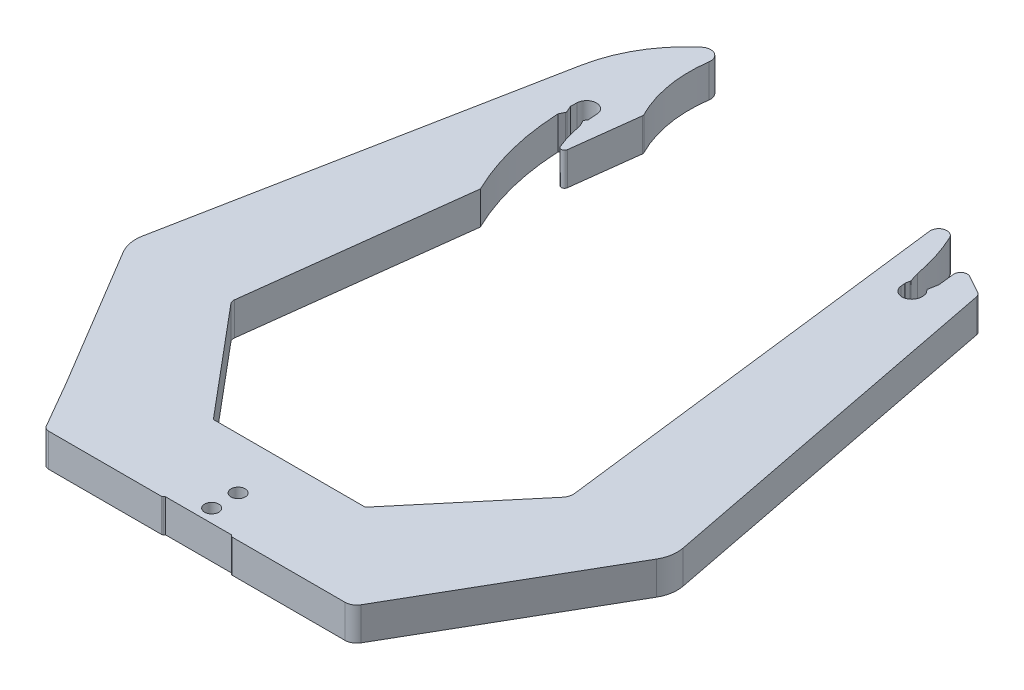
SolidWorks part; units mm, degrees
ref_plane "前视基准面" through (0, 0, 0) normal (0, 0, 1) x (1, 0, 0)
ref_plane "上视基准面" through (0, 0, 0) normal (0, 1, 0) x (1, 0, 0)
ref_plane "右视基准面" through (0, 0, 0) normal (1, 0, 0) x (0, 0, -1)
sketch "草图1" plane through (0, 0, 0) normal (0, 1, 0) x (1, 0, 0)
  line L0 (0, 0) -> (0, -28) construction
  line L1 (-23, 0) -> (23, 0)
  line L2 (-46.9156, -28) -> (46.9156, -28) construction
  line L3 (23, 0) -> (50.2804, 32.5116)
  line L4 (51.0926, 35.2535) -> (36.049, 157.7742)
  line L5 (47.9507, -26.2071) -> (80.6721, 30.468)
  line L6 (81.8281, 37.3761) -> (60.3948, 147.6409)
  line L7 (-10, -27.5) -> (10, -27.5)
  line L8 (10, -27.5) -> (10.3536, -27.8536)
  line L9 (10.7071, -28) -> (44.8453, -28)
  line L10 (-10, -27.5) -> (-10.3536, -27.8536)
  line L11 (-10.7071, -28) -> (-44.8453, -28)
  line L12 (-46.9156, -28) -> (-80.6721, 30.468) construction
  line L13 (-23, 0) -> (-50.7237, 33.0398)
  line L14 (-51.2827, 33.706) -> (-36.049, 157.7742) construction
  line L15 (-81.8281, 37.3761) -> (-60.2169, 148.5563)
  line L16 (52.0874, 139.7007) -> (51.9688, 140.8286)
  line L17 (53.9563, 152.0266) -> (59.4012, 149.0085)
  line L18 (-37.6333, 144.8711) -> (-51.1767, 34.5691)
  line L26 (-80.6721, 30.468) -> (-54.7279, -12.8828)
  line L27 (-54.7279, -12.8828) -> (-46.5774, -27)
  line L29 (51.518, 145.1181) -> (50.9977, 150.0683)
  line L38 (45.9622, 140.5216) -> (46.0104, 140.2189)
  line L40 (45.9622, 140.5216) -> (46.2393, 141.7564)
  line L41 (46.2287, 142.015) -> (45.3363, 144.8711)
  line L42 (51.518, 145.1181) -> (51.0019, 142.3738)
  line L43 (51.0952, 141.979) -> (51.9688, 140.8286)
  arc A0 (80.6721, 30.468) -> (81.8281, 37.3761) centre (72.0119, 35.468) ccw
  arc A1 (-80.6721, 30.468) -> (-81.8281, 37.3761) centre (-72.0119, 35.468) cw
  arc A2 (36.049, 157.7742) -> (40.7995, 159.1281) centre (38.5304, 158.0789) cw
  arc A3 (40.7995, 159.1281) -> (45.3363, 144.8711) centre (-13.661, 133.9476) cw
  arc A4 (46.115, 139.1281) -> (52.0874, 139.7007) centre (49.1038, 139.3871) ccw
  arc A5 (60.3948, 147.6409) -> (59.4012, 149.0085) centre (58.4316, 147.2592) ccw
  arc A6 (50.9977, 150.0683) -> (53.9563, 152.0266) centre (52.9867, 150.2774) cw
  arc A7 (-60.2169, 148.5563) -> (-46.6353, 171.5892) centre (-20.9518, 140.924) cw
  arc A8 (-46.6353, 171.5892) -> (-41.7383, 168.8711) centre (-44.709, 169.2893) cw
  arc A9 (-41.7383, 168.8711) -> (-37.6333, 144.8711) centre (-2.1289, 163.295) ccw
  arc A10 (-50.7237, 33.0398) -> (-51.1767, 34.5691) centre (-49.1916, 34.3254) cw
  arc A19 (47.9507, -26.2071) -> (44.8453, -28) centre (44.8453, -24.4141) cw
  arc A20 (50.2804, 32.5116) -> (51.0926, 35.2535) centre (47.5335, 34.8165) ccw
  arc A21 (10.3536, -27.8536) -> (10.7071, -28) centre (10.7071, -27.5) ccw
  arc A22 (-10.3536, -27.8536) -> (-10.7071, -28) centre (-10.7071, -27.5) cw
  arc A23 (-44.8453, -28) -> (-46.5774, -27) centre (-44.8453, -26) cw
  arc A29 (46.0104, 140.2189) -> (46.115, 139.1281) centre (-13.661, 133.9476) cw
  arc A32 (51.0019, 142.3738) -> (51.0952, 141.979) centre (51.4933, 142.2814) ccw
  arc A33 (46.2393, 141.7564) -> (46.2287, 142.015) centre (45.7514, 141.8658) ccw
  point P7 (0, 0)
  point P9 (0, -28)
  point P18 (82.5415, 33.706)
  point P24 (0, -27.5)
  point P50 (60.2169, 148.5563)
  point P53 (50.5961, 153.8892)
  point P56 (50.9609, 142.1557)
  point P65 (46.2686, 141.8871)
  point P76 (-54.6473, -14.6083)
  point P85 (51.2827, 33.706)
  point P88 (10.5, -28)
  point P91 (-10.5, -28)
  dimension "D14" = 10
  dimension "D17" = 2.5
  dimension "D18" = 3
  dimension "D20" = 60
  dimension "D22" = 2
  dimension "D23" = 40
  dimension "D24" = 3
  dimension "D26" = 40
  dimension "D30" = 2
  dimension "D39" = 0.5
  dimension "D28" = 2
  dimension "D33" = 150
  dimension "D34" = 4.7
  dimension "D35" = 0.5
  dimension "D1" = 28
  dimension "D2" = 46
  dimension "D4" = 130
  dimension "D5" = 44
  dimension "D6" = 133
  dimension "D7" = 125
  dimension "D8" = 120
  dimension "D9" = 139
  dimension "D10" = 117
  dimension "D11" = 10
  dimension "D12" = 1
  dimension "D13" = 135
  dimension "D15" = 130
  dimension "D16" = 55
  dimension "D19" = 20
  dimension "D21" = 11
  dimension "D25" = 13
  dimension "D27" = 24
  dimension "D29" = 34.1382
  dimension "D31" = 34.1382
extrude "凸台-拉伸1" add sketch "草图1" along normal blind 10
sketch "草图2" plane through (0, 10, 0) normal (0, 1, 0) x (1, 0, 0)
  line L0 (-51.1767, 34.5691) -> (-37.6333, 144.8711) construction
  line L1 (-44.9653, 137.163) -> (-44.8045, 135.3458)
  line L2 (-40.5801, 120.8711) -> (-43.0358, 100.8711)
  line L3 (-10, -27.5) -> (10, -27.5) construction
  line L4 (23, 0) -> (-23, 0) construction
  line L5 (-51.0321, 136.1605) -> (-50.2132, 134.2715)
  line L6 (-50.2197, 133.8595) -> (-50.959, 132.2906)
  line L7 (-44.8045, 135.3458) -> (-45.2779, 134.5968)
  line L8 (-45.298, 134.0972) -> (-44.4522, 132.4865)
  arc A0 (-43.0358, 100.8711) -> (-50.959, 132.2906) centre (28.9667, 135.7371) cw
  arc A1 (-50.9987, 138.0882) -> (-45.0011, 138.0823) centre (-48, 138) cw
  arc A2 (-45.0011, 138.0823) -> (-44.9653, 137.163) centre (-5.0162, 139.1798) ccw
  circle A3 centre (0, -23.5) radius 2.15
  circle A4 centre (0, -15.5) radius 2.15
  arc A7 (-44.4522, 132.4865) -> (-40.5801, 120.8711) centre (-5.0162, 139.1798) ccw
  arc A9 (-45.2779, 134.5968) -> (-45.298, 134.0972) centre (-44.8553, 134.3297) ccw
  arc A10 (-50.2132, 134.2715) -> (-50.2197, 133.8595) centre (-50.672, 134.0727) cw
  arc A11 (-51.0321, 136.1605) -> (-50.9987, 138.0882) centre (28.9667, 135.7371) cw
  point P28 (-45.4343, 134.3568)
  point P32 (-45.4322, 134.3528)
  point P35 (-50.1233, 134.0641)
  dimension "D5" = 3
  dimension "D6" = 138
  dimension "50" = 40
  dimension "D7" = 80
  dimension "D9" = 4.3
  dimension "D12" = 4.7
  dimension "D14" = 0.5
  dimension "D2" = 20
  dimension "D3" = 24
  dimension "D4" = 48
  dimension "D8" = 8
  dimension "D10" = 4
  dimension "D13" = 120
extrude "切除-拉伸1" cut sketch "草图2" against normal up to next
fillet "圆角1" radius 1 2 edges at (-37.6333, 5, -144.8711) (-40.5801, 5, -120.8711)
